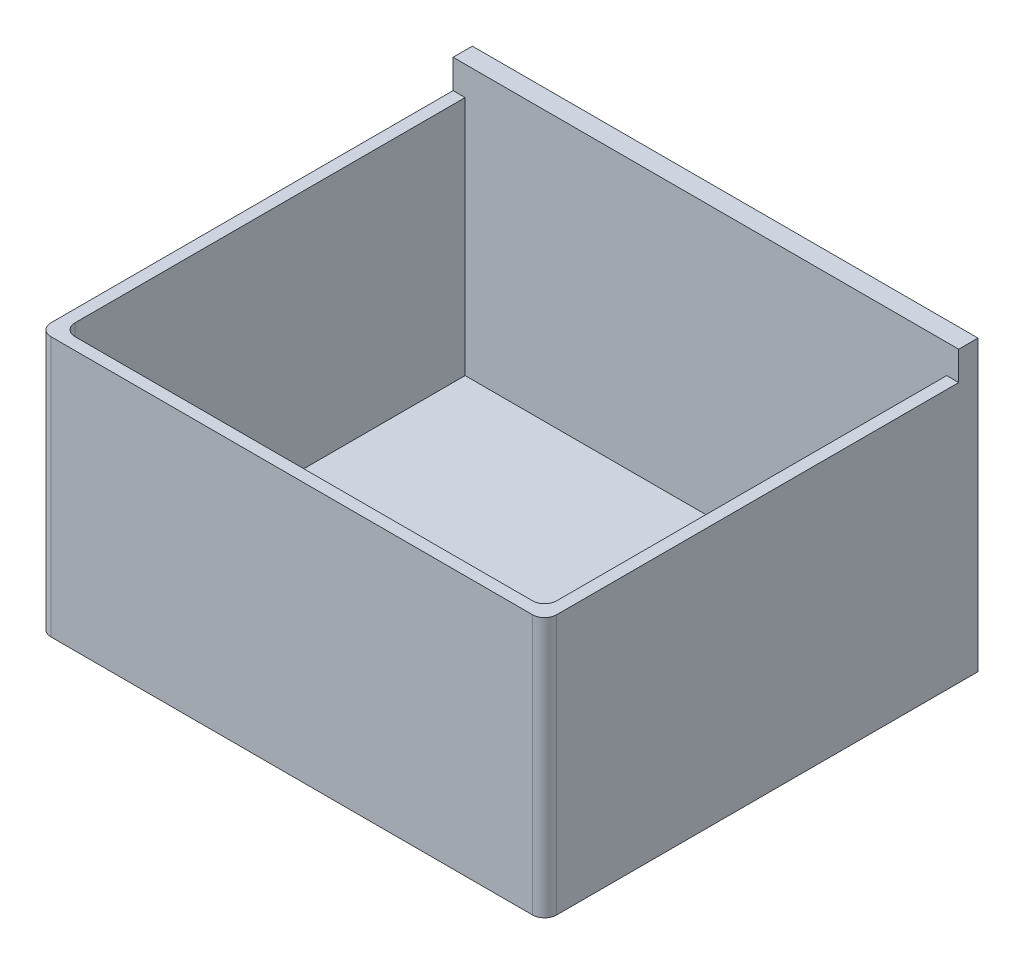
SolidWorks part; units mm, degrees
ref_plane "Front Plane" through (0, 0, 0) normal (0, 0, 1) x (1, 0, 0)
ref_plane "Top Plane" through (0, 0, 0) normal (0, 1, 0) x (1, 0, 0)
ref_plane "Right Plane" through (0, 0, 0) normal (1, 0, 0) x (0, 0, -1)
sketch "Sketch1" plane through (0, 0, 0) normal (1, 0, 0) x (0, 0, -1)
  line L0 (0, 0) -> (0, 120)
  line L1 (0, 120) -> (-8, 120)
  line L2 (-8, 120) -> (-8, 8)
  line L3 (-8, 8) -> (-180, 8)
  line L4 (-180, 8) -> (-180, 0)
  line L5 (-180, 0) -> (0, 0)
  dimension "D1" = 8
  dimension "D2" = 8
  dimension "D3" = 120
  dimension "D4" = 180
extrude "Boss-Extrude1" add sketch "Sketch1" along normal blind 210
sketch "Sketch2" plane through (0, 8, 0) normal (0, 1, 0) x (1, 0, 0)
  line L4 (5, -8) -> (5, -175)
  line L5 (5, -175) -> (205, -175)
  line L6 (205, -175) -> (205, -8)
  line L7 (5, -8) -> (0, -8)
  line L8 (0, -8) -> (0, -180)
  line L9 (0, -180) -> (210, -180)
  line L10 (210, -180) -> (210, -8)
  line L11 (210, -8) -> (0, -8)
  line L12 (0, -8) -> (0, -180)
  line L13 (0, -180) -> (210, -180)
  line L14 (210, -180) -> (210, -8)
  line L16 (210, -8) -> (205, -8)
  dimension "D1" = 0
  dimension "D2" = 5
extrude "Boss-Extrude2" add sketch "Sketch2" along normal blind 100
sketch "Sketch3" plane through (0, 0, 0) normal (0, -1, 0) x (1, 0, 0)
  line L0 (0, 140) -> (210, 140) construction
  line L1 (0, 180) -> (0, 0) construction
  line L2 (210, 180) -> (210, 0) construction
  line L3 (210, 180) -> (0, 180) construction
  line L4 (105, 180) -> (105, 0) construction
  line L5 (210, 0) -> (0, 0) construction
  line L6 (52.5, 180) -> (52.5, 0) construction
  line L7 (157.5, 180) -> (157.5, 0) construction
  circle A0 centre (24, 140) radius 2.75
  circle A1 centre (81, 140) radius 2.75
  circle A4 centre (81, 140) radius 2.75
  circle A5 centre (24, 140) radius 2.75
  circle A6 centre (186, 140) radius 2.75
  circle A7 centre (129, 140) radius 2.75
  dimension "D2" = 5.5
  dimension "D1" = 40
  dimension "D3" = 57
  dimension "D5" = 52.5
extrude "Cut-Extrude1" cut sketch "Sketch3" against normal blind 20 contours A0 | A1 | A7 | A6
fillet "Fillet1" radius 5 4 edges at (5, 58, 175) (0, 54, 180) (205, 58, 175) (210, 54, 180)
